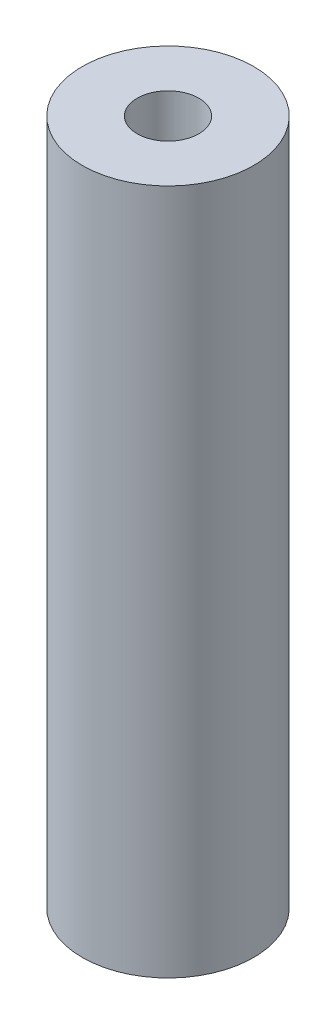
SolidWorks part; units mm, degrees
ref_plane "前视基准面" through (0, 0, 0) normal (0, 0, 1) x (1, 0, 0)
ref_plane "上视基准面" through (0, 0, 0) normal (0, 1, 0) x (1, 0, 0)
ref_plane "右视基准面" through (0, 0, 0) normal (1, 0, 0) x (0, 0, -1)
sketch "草图1" plane through (0, 0, 0) normal (0, 1, 0) x (1, 0, 0)
  circle A0 centre (0, 0) radius 50
  circle A1 centre (0, 0) radius 18
  dimension "D1" = 100
  dimension "D2" = 36
extrude "凸台-拉伸1" add sketch "草图1" along normal blind 400 contours A0
